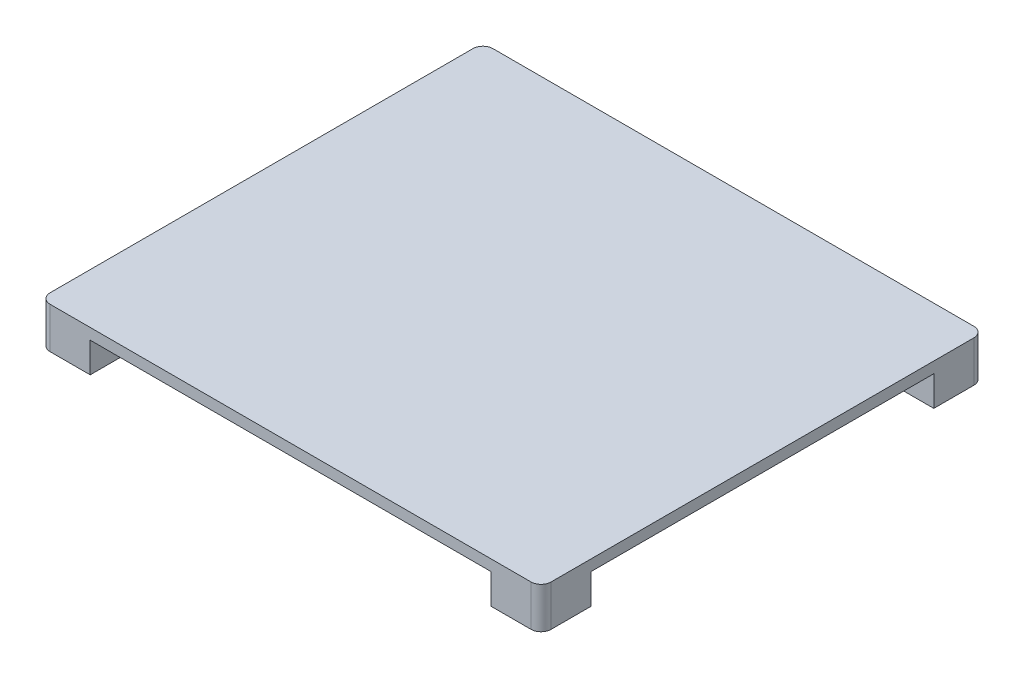
SolidWorks part; units mm, degrees
ref_plane "Alzado" through (0, 0, 0) normal (0, 0, 1) x (1, 0, 0)
ref_plane "Planta" through (0, 0, 0) normal (0, 1, 0) x (1, 0, 0)
ref_plane "Vista lateral" through (0, 0, 0) normal (1, 0, 0) x (0, 0, -1)
sketch "Croquis1" plane through (0, 0, 0) normal (0, 1, 0) x (1, 0, 0)
  line L1 (-125, -110.5) -> (125, -110.5)
  line L2 (-125, -110.5) -> (-125, 110.5)
  line L3 (-125, 110.5) -> (125, 110.5)
  line L4 (125, -110.5) -> (125, 110.5)
  line L5 (-125, -110.5) -> (125, 110.5) construction
  line L6 (-125, 110.5) -> (125, -110.5) construction
  point P0 (0, 0)
  dimension "D1" = 250
  dimension "D2" = 221
extrude "Saliente-Extruir1" add sketch "Croquis1" along normal blind 5.5
sketch "Croquis2" plane through (0, 0, 0) normal (0, -1, 0) x (1, 0, 0)
  line L0 (-125, 110.5) -> (-100, 110.5)
  line L1 (-125, 110.5) -> (125, 110.5) construction
  line L2 (-100, 110.5) -> (-100, 90.5)
  line L3 (-100, 90.5) -> (-105, 90.5)
  line L4 (-105, 90.5) -> (-105, 85.5)
  line L5 (-105, 85.5) -> (-125, 85.5)
  line L6 (-125, -110.5) -> (-125, 110.5) construction
  line L7 (-125, 85.5) -> (-125, 110.5)
  line L8 (125, -110.5) -> (125, -85.5)
  line L9 (125, 110.5) -> (125, -110.5) construction
  line L10 (125, -85.5) -> (105, -85.5)
  line L11 (105, -85.5) -> (105, -90.5)
  line L12 (105, -90.5) -> (100, -90.5)
  line L13 (100, -90.5) -> (100, -110.5)
  line L14 (125, -110.5) -> (-125, -110.5) construction
  line L15 (100, -110.5) -> (125, -110.5)
  dimension "D1" = 25
  dimension "D2" = 25
  dimension "D3" = 20
  dimension "D4" = 20
  dimension "D5" = 25
  dimension "D6" = 25
  dimension "D7" = 20
  dimension "D8" = 20
extrude "Saliente-Extruir2" add sketch "Croquis2" along normal blind 15
mirror "Simetría1" about plane through (0, 0, 0) normal (0, 0, 1) of "Saliente-Extruir2"
sketch "Croquis3" plane through (0, 0, 0) normal (0, -1, 0) x (1, 0, 0)
  line L1 (-75, -50) -> (75, -50)
  line L2 (-75, -50) -> (-75, 50)
  line L3 (-75, 50) -> (75, 50)
  line L4 (75, -50) -> (75, 50)
  line L5 (-75, -50) -> (75, 50) construction
  line L6 (-75, 50) -> (75, -50) construction
  point P0 (0, 0)
  dimension "D1" = 150
  dimension "D2" = 100
extrude "Saliente-Extruir3" add sketch "Croquis3" along normal blind 15
fillet "Fillet1" radius 5 4 edges at (-125, -4.75, 110.5) (-125, -4.75, -110.5) (125, -4.75, -110.5) (125, -4.75, 110.5)
